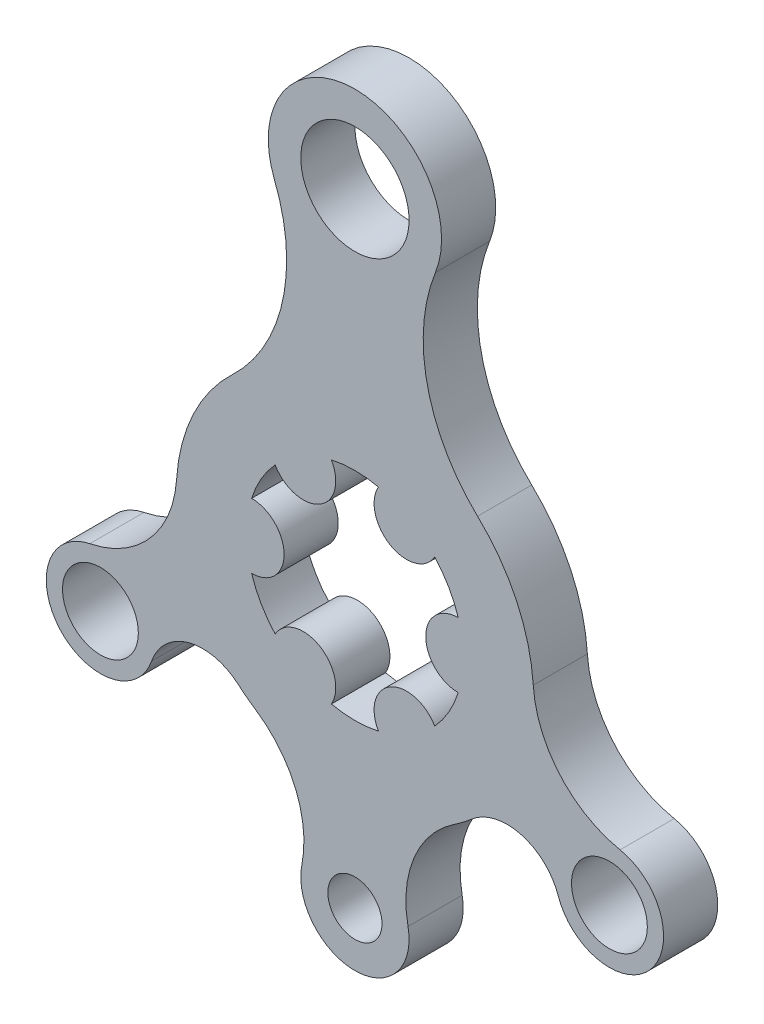
SolidWorks part; units mm, degrees
ref_plane "Front Plane" through (0, 0, 0) normal (0, 0, 1) x (1, 0, 0)
ref_plane "Top Plane" through (0, 0, 0) normal (0, 1, 0) x (1, 0, 0)
ref_plane "Right Plane" through (0, 0, 0) normal (1, 0, 0) x (0, 0, -1)
sketch "Sketch1" plane through (0, 0, 0) normal (0, 0, 1) x (1, 0, 0)
  line L0 (0, 0) -> (62110.9604, 0) construction
  line L1 (0, 0) -> (0, 62110.9604) construction
  line L2 (-1020.3224, -26) -> (-20.3224, -26) construction
  arc A0 (-19.0788, -6) -> (-14.7355, -13.5227) centre (0, 0) ccw
  arc A1 (-22.6472, 24.0021) -> (-33, 0) centre (0, 0) ccw
  arc A2 (-19.0788, -6) -> (-19.0788, 6) centre (-19.0788, 0) ccw
  arc A3 (-14.7355, 13.5227) -> (-4.3432, 19.5227) centre (-9.5394, 16.5227) ccw
  arc A4 (4.3432, 19.5227) -> (14.7355, 13.5227) centre (9.5394, 16.5227) ccw
  arc A5 (19.0788, 6) -> (19.0788, -6) centre (19.0788, 0) ccw
  arc A6 (14.7355, -13.5227) -> (4.3432, -19.5227) centre (9.5394, -16.5227) ccw
  arc A7 (-4.3432, -19.5227) -> (-14.7355, -13.5227) centre (-9.5394, -16.5227) ccw
  arc A8 (-14.7355, 13.5227) -> (-19.0788, 6) centre (0, 0) ccw
  arc A9 (4.3432, 19.5227) -> (-4.3432, 19.5227) centre (0, 0) ccw
  arc A10 (19.0788, 6) -> (14.7355, 13.5227) centre (0, 0) ccw
  arc A11 (-4.3432, -19.5227) -> (4.3432, -19.5227) centre (0, 0) ccw
  arc A12 (14.7355, -13.5227) -> (19.0788, -6) centre (0, 0) ccw
  circle A13 centre (0, -50) radius 5
  arc A14 (-9.804, -48.03) -> (9.804, -48.03) centre (0, -50) ccw
  circle A15 centre (-47, -26) radius 7
  arc A16 (-48.9633, -16.1946) -> (-37, -26) centre (-47, -26) ccw
  arc A17 (-9.804, -48.03) -> (-18.3132, -27.4523) centre (-29.4121, -44.09) ccw
  arc A18 (-21.5665, -24.9777) -> (-37.5509, -29.2733) centre (-28.1018, -32.5467) ccw
  arc A19 (9.804, -48.03) -> (18.3132, -27.4523) centre (29.4121, -44.09) cw
  arc A20 (-48.9633, -16.1946) -> (-32.9314, 2.127) centre (-52.8898, 3.4162) ccw
  arc A21 (21.5665, -24.9777) -> (37.5509, -29.2733) centre (28.1018, -32.5467) cw
  circle A22 centre (47, -26) radius 7
  arc A23 (48.9633, -16.1946) -> (37.5509, -29.2733) centre (47, -26) cw
  arc A24 (48.9633, -16.1946) -> (32.9314, 2.127) centre (52.8898, 3.4162) cw
  circle A25 centre (0, 65) radius 10
  arc A26 (14.8694, 59.0923) -> (-14.8694, 59.0923) centre (0, 65) ccw
  arc A27 (-22.6472, 24.0021) -> (-14.8694, 59.0923) centre (-44.6082, 47.2769) ccw
  arc A28 (22.6472, 24.0021) -> (14.8694, 59.0923) centre (44.6082, 47.2769) cw
  arc A29 (18.3132, -27.4523) -> (21.5665, -24.9777) centre (0, 0) ccw
  arc A30 (33, 0) -> (22.6472, 24.0021) centre (0, 0) ccw
  arc A31 (-21.5665, -24.9777) -> (-18.3132, -27.4523) centre (0, 0) ccw
  arc A32 (-22.6472, 24.0021) -> (-33, 0) centre (0, 0) ccw
  arc A33 (18.3132, -27.4523) -> (21.5665, -24.9777) centre (0, 0) ccw
  arc A34 (33, 0) -> (22.6472, 24.0021) centre (0, 0) ccw
  point P27 (0, 0)
  point P33 (0, 0)
  point P51 (0, 0)
  dimension "D1" = 40
  dimension "D2" = 66
  dimension "D3" = 12
  dimension "D5" = 10
  dimension "D6" = 20
  dimension "D7" = 14
  dimension "D8" = 20
  dimension "D12" = 40
  dimension "D13" = 20
  dimension "D14" = 20
  dimension "D15" = 20
  dimension "D16" = 32
  dimension "D18" = 64
  dimension "D9" = 24
  dimension "D10" = 47
  dimension "D11" = 26
  dimension "D17" = 65
  dimension "D4" = 6
extrude "Boss-Extrude1" add sketch "Sketch1" along normal blind 10
